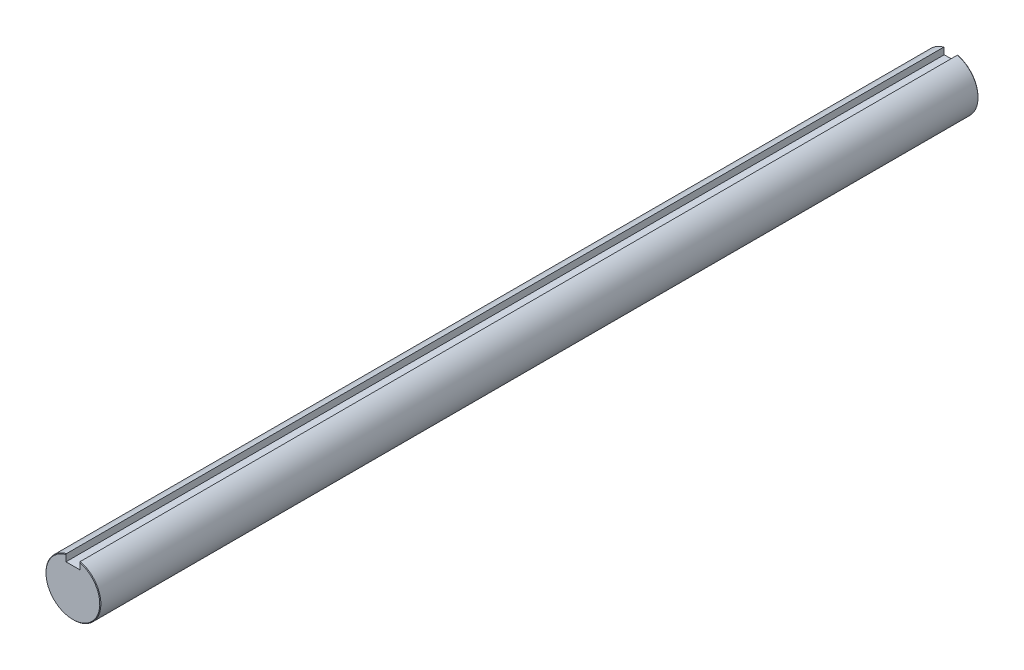
SolidWorks part; units mm, degrees
ref_plane "Front Plane" through (0, 0, 0) normal (0, 0, 1) x (1, 0, 0)
ref_plane "Top Plane" through (0, 0, 0) normal (0, 1, 0) x (1, 0, 0)
ref_plane "Right Plane" through (0, 0, 0) normal (1, 0, 0) x (0, 0, -1)
sketch "Sketch1" plane through (0, 0, 0) normal (1, 0, 0) x (0, 0, -1)
  line L0 (0, 0) -> (0, 4.7625) construction
  line L1 (-76.2, 4.7625) -> (76.2, 4.7625)
  line L2 (-76.2, 4.7625) -> (-76.2, -4.7625)
  line L3 (-76.2, -4.7625) -> (76.2, -4.7625)
  line L4 (76.2, 4.7625) -> (76.2, -4.7625)
  line L5 (-76.2, 4.7625) -> (76.2, -4.7625) construction
  line L6 (-76.2, -4.7625) -> (76.2, 4.7625) construction
  line L7 (0, 0) -> (0, -4.7625) construction
  point P0 (0, 0)
  dimension "Diameter" = 9.525
  dimension "Length" = 152.4
  dimension "Keyway Length" = 152.4
sketch "Sketch2" plane through (0, 0, 0) normal (0, 0, 1) x (1, 0, 0)
  line L0 (0, 0) -> (0, 4.7625) construction
  line L2 (1.1938, 3.4166) -> (-1.1938, 3.4166)
  line L3 (1.1938, 3.4166) -> (1.1938, 4.6104)
  line L4 (1.1938, 4.6104) -> (-1.1938, 4.6104)
  line L5 (-1.1938, 3.4166) -> (-1.1938, 4.6104)
  line L6 (1.1938, 3.4166) -> (-1.1938, 4.6104) construction
  line L7 (1.1938, 4.6104) -> (-1.1938, 3.4166) construction
  circle A0 centre (0, 0) radius 4.7625
  point P3 (0, 4.0135)
  dimension "Keyway Width" = 2.3876
  dimension "Keyway Depth" = 1.1938
sketch "Sketch3" plane through (0, 0, 0) normal (0, 0, 1) x (1, 0, 0)
  line L1 (-1.1938, 3.4166) -> (-1.1938, 4.6104) construction
  line L2 (1.1938, 3.4166) -> (-1.1938, 3.4166) construction
  line L3 (1.1938, 3.4166) -> (1.1938, 4.6104) construction
  line L5 (-1.1938, 3.4166) -> (-1.1938, 4.6104)
  line L6 (1.1938, 3.4166) -> (-1.1938, 3.4166)
  line L7 (1.1938, 3.4166) -> (1.1938, 4.6104)
  circle A0 centre (0, 0) radius 4.7625 construction
  arc A1 (-1.1938, 4.6104) -> (1.1938, 4.6104) centre (0, 0) ccw
extrude "Boss-Extrude1" add sketch "Sketch3" along normal up to vertex (76.2 mm away) and the other way up to vertex (76.2 mm away) up to point (0, 4.7625, 76.2) other way up to point (0, 4.7625, -76.2)
chamfer "Chamfer1" distance 0.0953 angle 45 2 edges at (0, -4.7625, 76.2) (0, -4.7625, -76.2)
equation "\"D1@Chamfer1\"=\"Diameter@Sketch1\"*.01"
